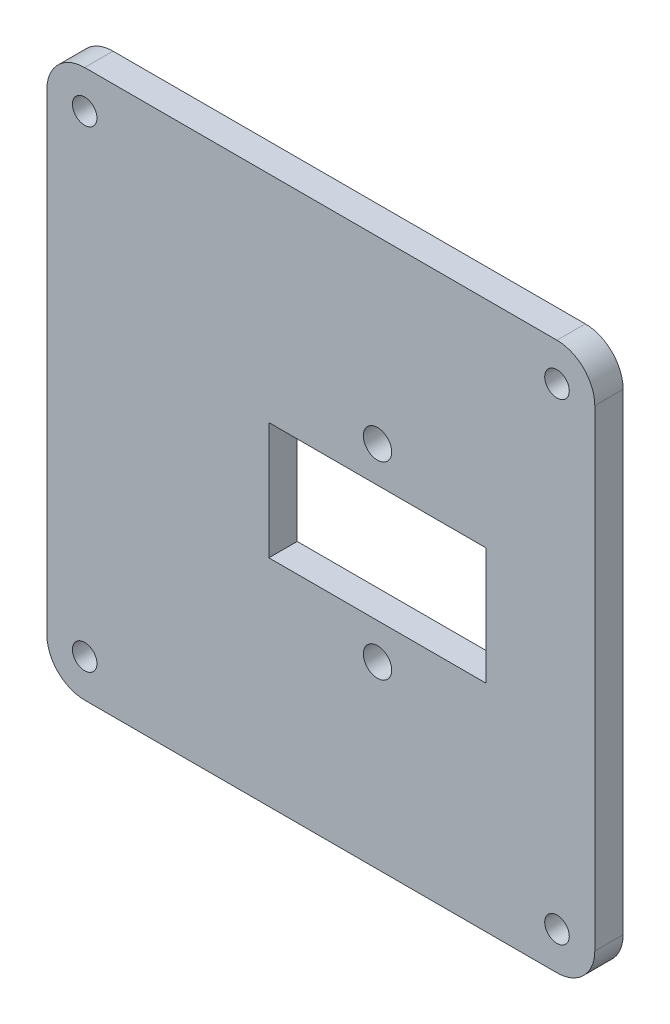
SolidWorks part; units mm, degrees
material "Acrílico (médio-alto impacto)"
ref_plane "Plano frontal" through (0, 0, 0) normal (0, 0, 1) x (1, 0, 0)
ref_plane "Plano superior" through (0, 0, 0) normal (0, 1, 0) x (1, 0, 0)
ref_plane "Plano direito" through (0, 0, 0) normal (1, 0, 0) x (0, 0, -1)
sketch "Esboço1" plane through (0, 0, 0) normal (0, 0, 1) x (1, 0, 0)
  line L1 (-29, -29) -> (29, -29)
  line L2 (-29, -29) -> (-29, 29)
  line L3 (-29, 29) -> (29, 29)
  line L4 (29, -29) -> (29, 29)
  line L5 (0, 29) -> (0, -29) construction
  line L6 (-29, 0) -> (29, 0) construction
  line L7 (-25, -25) -> (25, -25) construction
  line L8 (-25, -25) -> (-25, 25) construction
  line L9 (-25, 25) -> (25, 25) construction
  line L10 (25, -25) -> (25, 25) construction
  line L11 (0, 25) -> (0, -25) construction
  line L12 (-25, 0) -> (25, 0) construction
  point P0 (0, 0)
  point P4 (0, 0)
  dimension "D1" = 58
  dimension "D2" = 50
extrude "Ressalto-extrusão1" add sketch "Esboço1" along normal blind 3
hole_wizard "Furo de diâmetro Ø2.6 (2.6)1" positions "Esboço2" profile "Esboço3" hole size "Ø2.6" standard "ISO" end condition through all
sketch "Esboço2" plane through (0, 0, 3) normal (0, 0, 1) x (1, 0, 0)
  point P0 (-25, 25)
  point P3 (25, 25)
  point P6 (25, -25)
  point P9 (-25, -25)
sketch "Esboço3" plane through (-25, 25, 3) normal (1, 0, 0) x (0, -1, 0)
  line L0 (0, 0) -> (0, 3)
  line L1 (0, 3) -> (1.3, 3)
  line L2 (1.3, 3) -> (1.3, 0)
  line L5 (1.3, 0) -> (0, 0)
  line L11 (0, -6.35) -> (0, 107.95) construction
  dimension "Thru Hole Dia." = 2.6
  dimension "Thru Hole Depth" = 3
sketch "Perfil Corte" plane through (-34.6087, -26.1434, 3) normal (0, 0, 1) x (1, 0, 0)
  line L0 (40.6087, 16.1434) -> (40.6087, 36.1434) construction
  line L1 (29.1087, 19.9434) -> (52.1087, 19.9434)
  line L2 (29.1087, 19.9434) -> (29.1087, 32.3434)
  line L3 (29.1087, 32.3434) -> (52.1087, 32.3434)
  line L4 (52.1087, 19.9434) -> (52.1087, 32.3434)
  line L5 (40.6087, 32.3434) -> (40.6087, 19.9434) construction
  line L6 (29.1087, 26.1434) -> (52.1087, 26.1434) construction
  line L7 (52.1087, 26.1434) -> (63.6087, 26.1434) construction
  line L8 (63.6087, -2.8566) -> (63.6087, 55.1434) construction
  line L9 (63.6087, 55.1434) -> (5.6087, 55.1434) construction
  point P0 (40.6087, 26.1434)
  point P7 (40.6087, 26.1434)
  dimension "D1" = 23
  dimension "entre furos" = 20
  dimension "D2" = 12.4
  dimension "Afastamento Lateral" = 23
  dimension "Posicionamento Altura" = 29
extrude "Corte Principal" cut sketch "Perfil Corte" against normal through all
hole_wizard "Furo de diâmetro Ø3.0 (3)1" positions "Esboço4" profile "Esboço5" hole size "Ø3.0" standard "ISO" end condition through all
sketch "Esboço4" plane through (-55.0978, -24.4283, 3) normal (0, 0, 1) x (1, 0, 0)
  point P0 (61.0978, 34.4283)
  point P3 (61.0978, 14.4283)
sketch "Esboço5" plane through (6, 10, 3) normal (1, 0, 0) x (0, -1, 0)
  line L0 (0, 0) -> (0, 3)
  line L1 (0, 3) -> (1.5, 3)
  line L2 (1.5, 3) -> (1.5, 0)
  line L5 (1.5, 0) -> (0, 0)
  line L11 (0, -6.35) -> (0, 107.95) construction
  dimension "Thru Hole Dia." = 3
  dimension "Thru Hole Depth" = 3
other "Furos Motor<1>"
fillet "Filete1" radius 4 4 edges at (-29, -29, 1.5) (-29, 29, 1.5) (29, 29, 1.5) (29, -29, 1.5)
